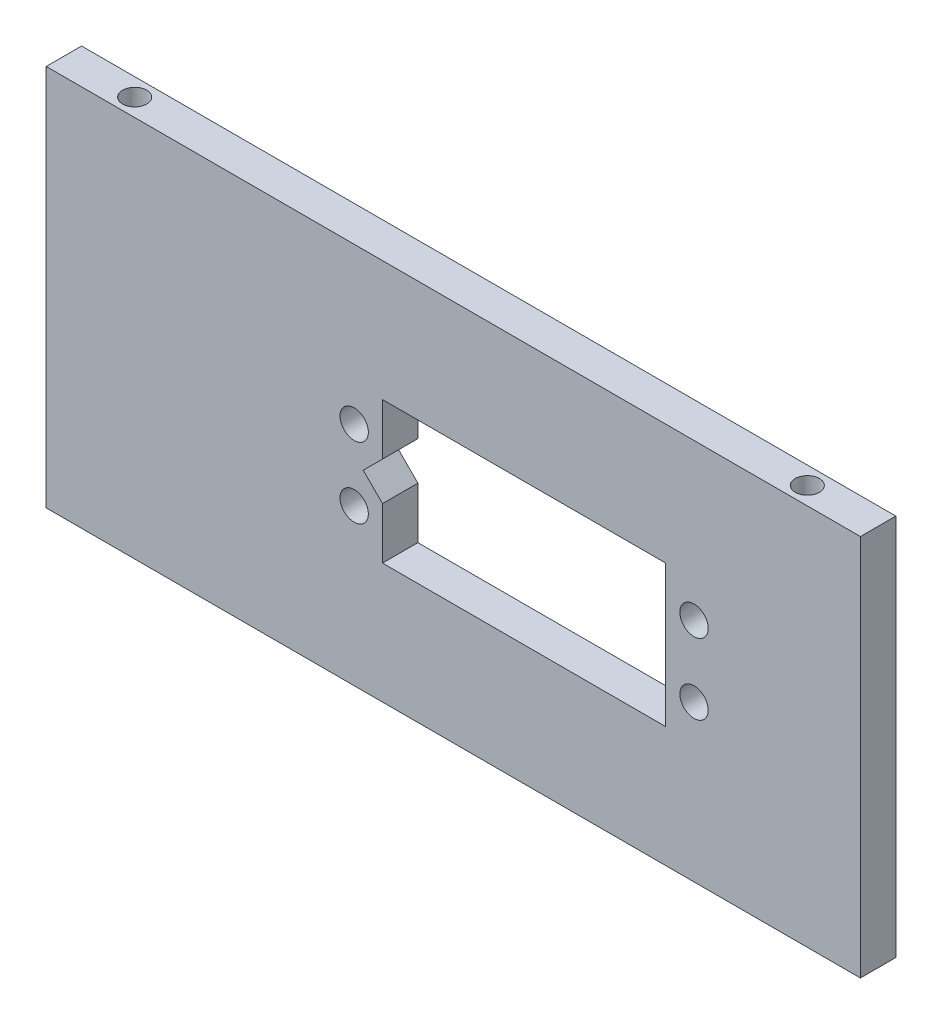
SolidWorks part; units mm, degrees
ref_plane "前基準面" through (0, 0, 0) normal (0, 0, 1) x (1, 0, 0)
ref_plane "上基準面" through (0, 0, 0) normal (0, 1, 0) x (1, 0, 0)
ref_plane "右基準面" through (0, 0, 0) normal (1, 0, 0) x (0, 0, -1)
sketch "草圖1" plane through (0, 0, 0) normal (0, 0, 1) x (1, 0, 0)
  line L1 (-44.4375, 23.5159) -> (70.5625, 23.5159)
  line L2 (-44.4375, 23.5159) -> (-44.4375, -30.4841)
  line L3 (-44.4375, -30.4841) -> (70.5625, -30.4841)
  line L4 (70.5625, 23.5159) -> (70.5625, -30.4841)
  line L5 (13.0625, -30.4841) -> (13.0625, 23.5159) construction
  line L6 (-44.4375, -3.4841) -> (70.5625, -3.4841) construction
  line L7 (3.0625, 6.5159) -> (43.0625, 6.5159)
  line L8 (3.0625, 6.5159) -> (3.0625, -13.4841)
  line L9 (3.0625, -13.4841) -> (43.0625, -13.4841)
  line L10 (43.0625, 6.5159) -> (43.0625, -13.4841)
  line L11 (23.0625, -13.4841) -> (23.0625, 6.5159) construction
  line L12 (3.0625, -3.4841) -> (43.0625, -3.4841) construction
  circle A0 centre (-0.9375, -8.4841) radius 2
  circle A1 centre (47.0625, -8.4841) radius 2
  circle A2 centre (-0.9375, 1.5159) radius 2
  circle A3 centre (47.0625, 1.5159) radius 2
  point P132 (23.0625, -3.4841)
  point P140 (13.0625, -3.4841)
  dimension "D5" = 4
  dimension "D9" = 4
  dimension "D1" = 115
  dimension "D2" = 54
  dimension "D3" = 20
  dimension "D4" = 40
  dimension "D6" = 48
  dimension "D7" = 4
  dimension "D8" = 10
  dimension "D10" = 5
  dimension "D11" = 5
  dimension "D12" = 10
  dimension "D16" = 48
extrude "填料-伸長3" add sketch "草圖1" along normal blind 5 contours A2 | A1 | A0 | L7 L10 L9 L8 | L1 L4 L3 L2 | A3
sketch "草圖3" plane through (0, -30.4841, 0) normal (0, -1, 0) x (1, 0, 0)
  line L0 (-44.4375, 5) -> (70.5625, 5) construction
  line L1 (70.5625, 5) -> (70.5625, 0) construction
  circle A0 centre (29.0625, 2.5) radius 1.75
  circle A1 centre (-2.9375, 2.5) radius 1.75
  dimension "D1" = 3.5
  dimension "D2" = 2.5
  dimension "D3" = 32
  dimension "D4" = 41.5
extrude "除料-伸長2" cut sketch "草圖3" against normal blind 15 contours A1 | A0
sketch "草圖4" plane through (0, 0, 5) normal (0, 0, 1) x (1, 0, 0)
  line L1 (3.0625, 6.5159) -> (3.0625, -13.4841) construction
  line L2 (0.3407, -3.4841) -> (3.0625, -6.2059)
  line L3 (3.0625, -6.2059) -> (3.0625, -0.7623)
  line L4 (3.0625, -0.7623) -> (0.3407, -3.4841)
extrude "除料-伸長3" cut sketch "草圖4" against normal blind 10
sketch "草圖5" plane through (0, 23.5159, 0) normal (0, 1, 0) x (1, 0, 0)
  line L0 (-44.4375, -5) -> (70.5625, -5) construction
  line L1 (-44.4375, -5) -> (-44.4375, 0) construction
  line L2 (70.5625, -5) -> (70.5625, 0) construction
  circle A0 centre (-34.4375, -2.5) radius 1.7
  circle A1 centre (60.5625, -2.5) radius 1.7
  dimension "D1" = 3.4
  dimension "D4" = 3.4
  dimension "D2" = 2.5
  dimension "D3" = 10
  dimension "D5" = 10
  dimension "D6" = 2.5
  dimension "D7" = 95
extrude "除料-伸長4" cut sketch "草圖5" against normal blind 10 contours A1 | A0
